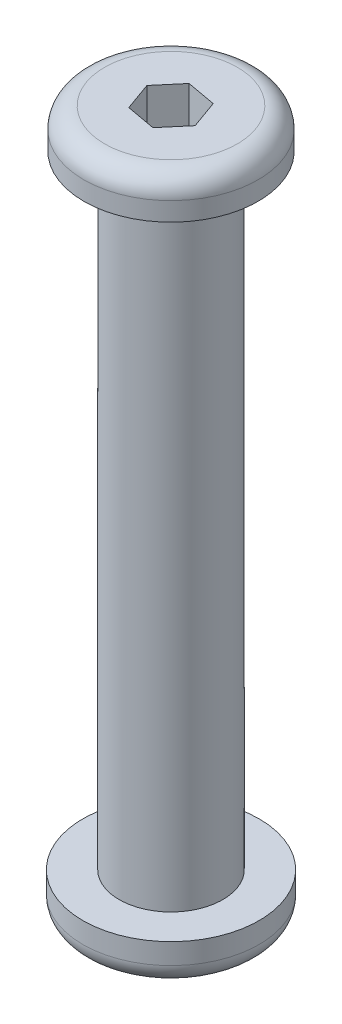
SolidWorks part; units mm, degrees
material "AISI 304"
ref_plane "前视基准面" through (0, 0, 0) normal (0, 0, 1) x (1, 0, 0)
ref_plane "上视基准面" through (0, 0, 0) normal (0, 1, 0) x (1, 0, 0)
ref_plane "右视基准面" through (0, 0, 0) normal (1, 0, 0) x (0, 0, -1)
other "Configuration Table"
sketch "草图1" plane through (0, 0, 0) normal (0, 1, 0) x (1, 0, 0)
  circle A0 centre (0, 0) radius 2.5
  dimension "D1" = 5
extrude "凸台-拉伸1" add sketch "草图1" along normal blind 30
sketch "草图2" plane through (0, 30, 0) normal (0, 1, 0) x (1, 0, 0)
  line L1 (0.9335, 1.1008) -> (-0.4866, 1.3589)
  line L2 (-0.4866, 1.3589) -> (-1.4201, 0.258)
  line L3 (-1.4201, 0.258) -> (-0.9335, -1.1008)
  line L4 (-0.9335, -1.1008) -> (0.4866, -1.3589)
  line L5 (0.4866, -1.3589) -> (1.4201, -0.258)
  line L6 (1.4201, -0.258) -> (0.9335, 1.1008)
  circle A0 centre (0, 0) radius 4.2
  circle A1 centre (0, 0) radius 1.25 construction
  dimension "D1" = 8.4
  dimension "D2" = 2.5
extrude "凸台-拉伸2" add sketch "草图2" along normal blind 1.9
sketch "草图3" plane through (0, 0, 0) normal (0, -1, 0) x (1, 0, 0)
  line L1 (0.8318, 1.1796) -> (-0.6057, 1.3102)
  line L2 (-0.6057, 1.3102) -> (-1.4375, 0.1305)
  line L3 (-1.4375, 0.1305) -> (-0.8318, -1.1796)
  line L4 (-0.8318, -1.1796) -> (0.6057, -1.3102)
  line L5 (0.6057, -1.3102) -> (1.4375, -0.1305)
  line L6 (1.4375, -0.1305) -> (0.8318, 1.1796)
  circle A0 centre (0, 0) radius 4.25
  circle A1 centre (0, 0) radius 1.25 construction
  dimension "D1" = 8.5
  dimension "D2" = 2.5
extrude "凸台-拉伸3" add sketch "草图3" along normal blind 2
fillet "圆角1" radius 1 2 edges at (0, 31.9, 4.2) (0, -2, -4.25)
